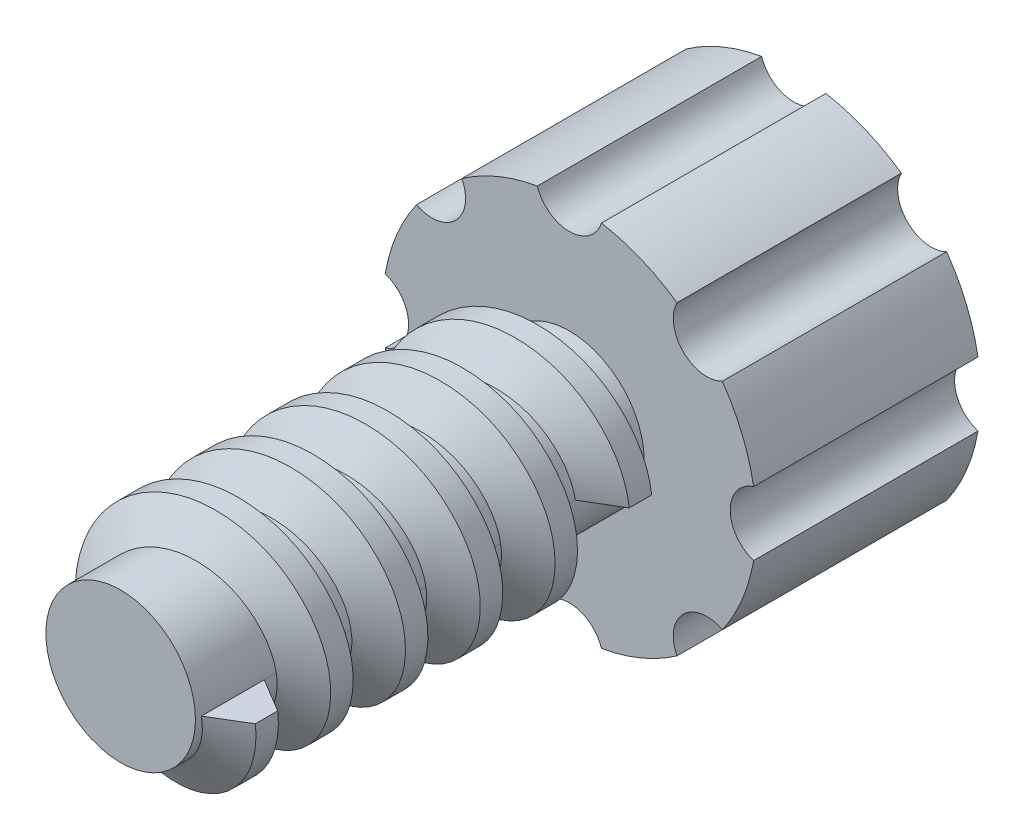
SolidWorks part; units mm, degrees
ref_plane "Front Plane" through (0, 0, 0) normal (0, 0, 1) x (1, 0, 0)
ref_plane "Top Plane" through (0, 0, 0) normal (0, 1, 0) x (1, 0, 0)
ref_plane "Right Plane" through (0, 0, 0) normal (1, 0, 0) x (0, 0, -1)
sketch "Sketch1" plane through (0, 0, 0) normal (0, 0, 1) x (1, 0, 0)
  circle A0 centre (0, 0) radius 2.5
extrude "Compact_head_D5_H3" add sketch "Sketch1" along normal blind 3 from offset 3
sketch "Sketch2" plane through (0, 0, 0) normal (0, 0, 1) x (1, 0, 0)
  circle A0 centre (0, 0) radius 1
extrude "Printed_screw_core_D2" add sketch "Sketch2" along normal blind 6 from offset 0
ref_plane "Actual_printed_thread_D2p9_P1_start_plane" through (0, 0, 0.5) normal (0, 0, 1) x (1, 0, 0)
sketch "Sketch3" plane through (0, 0, 0.5) normal (0, 0, 1) x (1, 0, 0)
  circle A0 centre (0, 0) radius 0.98
curve "Actual_printed_thread_D2p9_P1_helix" pitch 1 height 5 turns 5
sketch3d "3DSketch1"
  line L0 (0.95, 0, 0.05) -> (1.45, 0, 0.35)
  line L1 (1.45, 0, 0.35) -> (1.45, 0, 0.65)
  line L2 (1.45, 0, 0.65) -> (0.95, 0, 0.95)
  line L3 (0.95, 0, 0.95) -> (0.95, 0, 0.05)
sweep "Actual_printed_thread_D2p9_P1" add profiles "3DSketch1" path "Actual_printed_thread_D2p9_P1_helix"
sketch "Sketch4" plane through (0, 0, 0) normal (0, 0, 1) x (1, 0, 0)
  circle A0 centre (2.6, 0) radius 0.45
  circle A1 centre (1.8385, 1.8385) radius 0.45
  circle A2 centre (0, 2.6) radius 0.45
  circle A3 centre (-1.8385, 1.8385) radius 0.45
  circle A4 centre (-2.6, 0) radius 0.45
  circle A5 centre (-1.8385, -1.8385) radius 0.45
  circle A6 centre (0, -2.6) radius 0.45
  circle A7 centre (1.8385, -1.8385) radius 0.45
extrude "Small_finger_grip_flutes" cut sketch "Sketch4" along normal blind 3 from offset 3
